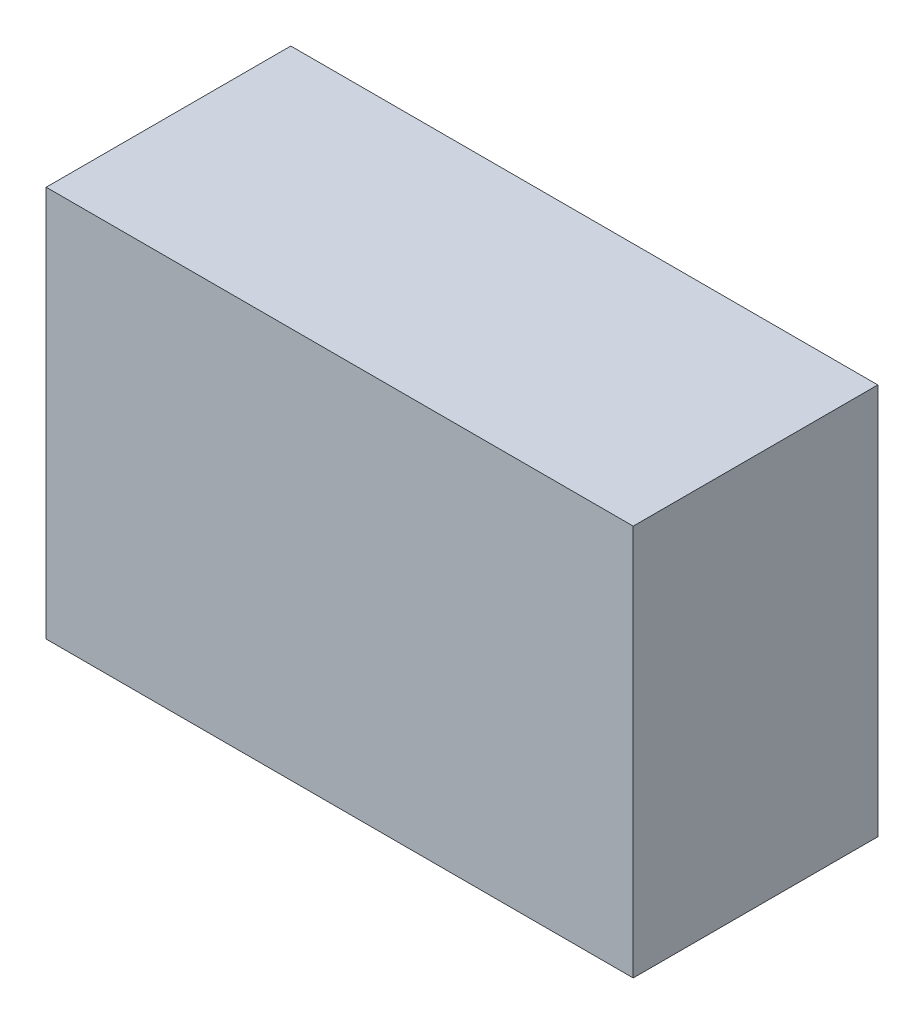
SolidWorks part; units mm, degrees
ref_plane "前视基准面" through (0, 0, 0) normal (0, 0, 1) x (1, 0, 0)
ref_plane "上视基准面" through (0, 0, 0) normal (0, 1, 0) x (1, 0, 0)
ref_plane "右视基准面" through (0, 0, 0) normal (1, 0, 0) x (0, 0, -1)
other "Configuration Table"
sketch "草图1" plane through (0, 0, 0) normal (0, 0, 1) x (1, 0, 0)
  line L0 (0, 0) -> (12, 0)
  line L1 (12, 0) -> (12, 8)
  line L2 (12, 8) -> (0, 8)
  line L3 (0, 8) -> (0, 0)
  dimension "width" = 12
  dimension "height" = 8
extrude "Cable_Clamp" add sketch "草图1" along normal blind 5
